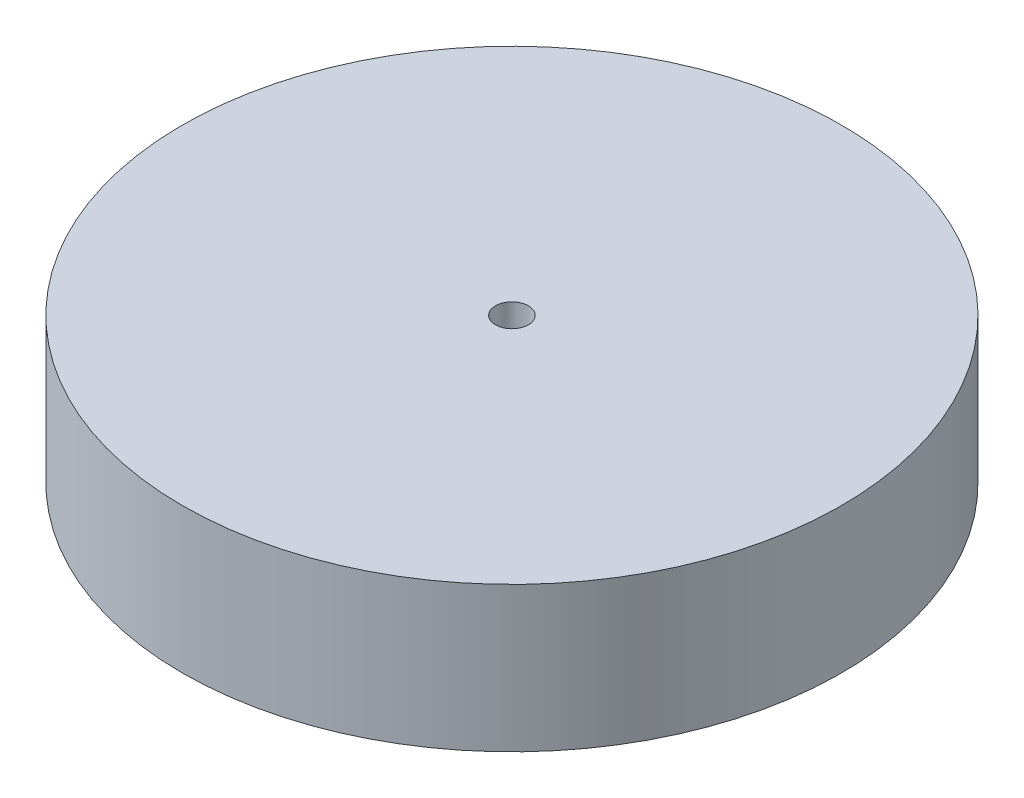
SolidWorks part; units mm, degrees
ref_plane "Plan de face" through (0, 0, 0) normal (0, 0, 1) x (1, 0, 0)
ref_plane "Plan de dessus" through (0, 0, 0) normal (0, 1, 0) x (1, 0, 0)
ref_plane "Plan de droite" through (0, 0, 0) normal (1, 0, 0) x (0, 0, -1)
sketch "Esquisse1" plane through (0, 0, 0) normal (0, 1, 0) x (1, 0, 0)
  circle A0 centre (0, 0) radius 50
extrude "Boss.-Extru.1" add sketch "Esquisse1" along normal blind 22
sketch "Esquisse4" plane through (0, 22, 0) normal (0, 1, 0) x (1, 0, 0)
  circle A0 centre (0, 0) radius 2.5
extrude "Enlèv. mat.-Extru.1" cut sketch "Esquisse4" against normal blind 7
sketch "Esquisse5" plane through (0, 0, 0) normal (0, -1, 0) x (-1, 0, 0)
  line L0 (1.6523, -1.8762) -> (2.4939, -0.1745)
  circle A0 centre (0, 0) radius 2.5
extrude "Enlèv. mat.-Extru.2" cut sketch "Esquisse5" against normal blind 15 contours L0 A0
